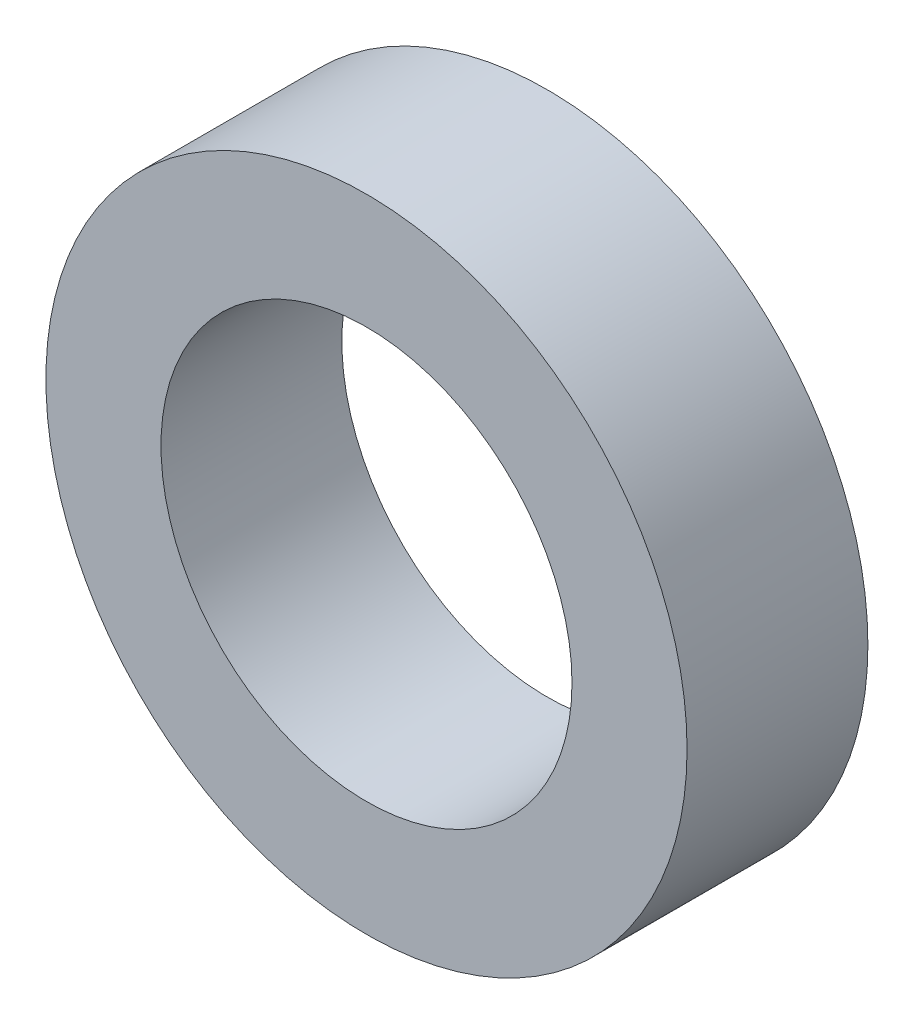
SolidWorks part; units mm, degrees
ref_plane "前视基准面" through (0, 0, 0) normal (0, 0, 1) x (1, 0, 0)
ref_plane "上视基准面" through (0, 0, 0) normal (0, 1, 0) x (1, 0, 0)
ref_plane "右视基准面" through (0, 0, 0) normal (1, 0, 0) x (0, 0, -1)
sketch "草图1" plane through (0, 0, 0) normal (0, 0, 1) x (1, 0, 0)
  circle A0 centre (0, 0) radius 39
  circle A1 centre (0, 0) radius 25
  dimension "D1" = 50
  dimension "D2" = 78
extrude "凸台-拉伸1" add sketch "草图1" along normal blind 22
